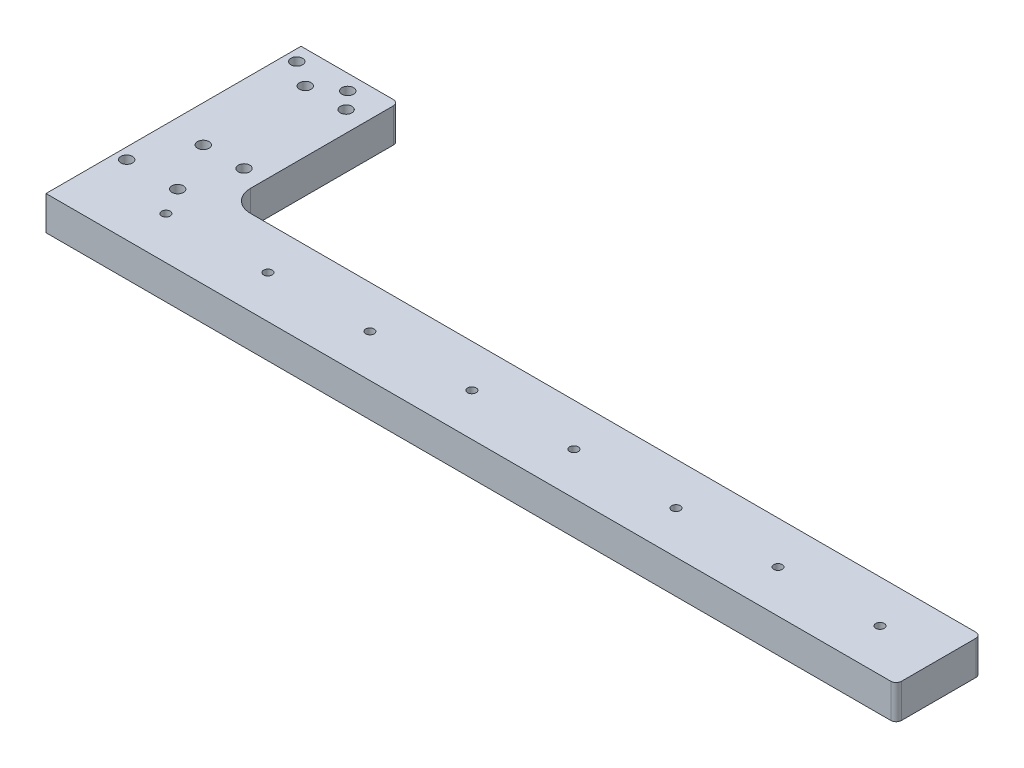
SolidWorks part; units mm, degrees
material "Low Carbon Steel"
ref_plane "Front Plane" through (0, 0, 0) normal (0, 0, 1) x (1, 0, 0)
ref_plane "Top Plane" through (0, 0, 0) normal (0, 1, 0) x (1, 0, 0)
ref_plane "Right Plane" through (0, 0, 0) normal (1, 0, 0) x (0, 0, -1)
sketch "Sketch1" plane through (0, 0, 0) normal (0, 1, 0) x (1, 0, 0)
  line L1 (0, 0) -> (496.825, 0)
  line L2 (0, 0) -> (0, 150)
  line L3 (0, 150) -> (54.325, 150)
  line L4 (500, 3.175) -> (500, 46.825)
  line L7 (496.825, 50) -> (70.2, 50)
  line L8 (57.5, 146.825) -> (57.5, 62.7)
  arc A0 (70.2, 50) -> (57.5, 62.7) centre (70.2, 62.7) cw
  arc A1 (496.825, 0) -> (500, 3.175) centre (496.825, 3.175) ccw
  arc A2 (500, 46.825) -> (496.825, 50) centre (496.825, 46.825) ccw
  arc A3 (57.5, 146.825) -> (54.325, 150) centre (54.325, 146.825) ccw
  point P12 (500, 0)
  dimension "D5" = 12.7
  dimension "D6" = 3.175
  dimension "D1" = 500
  dimension "D2" = 150
  dimension "D3" = 50
  dimension "D4" = 57.5
extrude "Boss-Extrude1" add sketch "Sketch1" along normal mid plane 20
hole_wizard "M6 Tapped Hole2" positions "Sketch2" profile "Sketch3" tap size "M6" standard "Peddi DIN"
sketch "Sketch2" plane through (0, 10, 0) normal (0, 1, 0) x (1, 0, 0)
  line L0 (0, 150) -> (0, 0) construction
  line L1 (0, 0) -> (496.825, 0) construction
  point P0 (45.5, 25)
  dimension "D1" = 45.5
  dimension "D2" = 25
cosmetic thread "Hole Thread1" parameters "D2"=6
sketch "Sketch3" plane through (45.5, 10, -25) normal (1, 0, 0) x (0, 0, 1)
  line L0 (0, 0) -> (0, 29.493)
  line L1 (0, 29.493) -> (2.5, 27.9908)
  line L2 (2.5, 27.9908) -> (2.5, 0)
  line L5 (2.5, 0) -> (0, 0)
  line L10 (0, 29.493) -> (-2.5, 27.9908) construction
  line L11 (0, -6.35) -> (0, 107.95) construction
  dimension "Tap Drill Dia." = 5
  dimension "Tap Drill Depth" = 27.9908
  dimension "Drill Angle" = 118
pattern_linear "LPattern2" count 8 spacing 60 along (1, 0, 0) of "M6 Tapped Hole2"
cosmetic thread "Hole Thread2" parameters "D2"=6
cosmetic thread "Hole Thread3" parameters "D2"=6
cosmetic thread "Hole Thread4" parameters "D2"=6
cosmetic thread "Hole Thread5" parameters "D2"=6
cosmetic thread "Hole Thread6" parameters "D2"=6
cosmetic thread "Hole Thread7" parameters "D2"=6
cosmetic thread "Hole Thread8" parameters "D2"=6
hole_wizard "M8 Tapped Hole2" positions "Sketch4" profile "Sketch5" tap size "M8" standard "Peddi DIN" end condition through all
sketch "Sketch4" plane through (0, 10, 0) normal (0, 1, 0) x (1, 0, 0)
  line L0 (45.5, 71) -> (45.5, 25) construction
  circle A0 centre (45.5, 25) radius 2.5 construction
  point P0 (45.5, 131)
  point P2 (21.5, 131)
  point P4 (45.5, 71)
  point P6 (21.5, 71)
  dimension "D3" = 46
  dimension "D1" = 24
  dimension "D2" = 60
cosmetic thread "Hole Thread9" parameters "D2"=8
cosmetic thread "Hole Thread10" parameters "D2"=8
cosmetic thread "Hole Thread11" parameters "D2"=8
cosmetic thread "Hole Thread12" parameters "D2"=8
sketch "Sketch5" plane through (45.5, 10, -131) normal (1, 0, 0) x (0, 0, 1)
  line L0 (0, 0) -> (0, 20)
  line L1 (0, 20) -> (3.4, 20)
  line L2 (3.4, 20) -> (3.4, 0)
  line L5 (3.4, 0) -> (0, 0)
  line L11 (0, -6.35) -> (0, 107.95) construction
  dimension "Thru Tap Drill Dia." = 6.8
  dimension "Thru Tap Drill Depth" = 20
hole_wizard "Ø6.8 (6.8) Diameter Hole1" positions "Sketch6" profile "Sketch7" hole size "Ø6.8" standard "Peddi DIN"
sketch "Sketch6" plane through (0, 10, 0) normal (0, 1, 0) x (1, 0, 0)
  circle A0 centre (45.5, 25) radius 2.5 construction
  point P0 (36.5, 140.95)
  point P2 (6.5, 140.95)
  point P4 (6.5, 40.95)
  point P6 (36.5, 40.95)
  dimension "D1" = 9
  dimension "D2" = 30
  dimension "D3" = 100
  dimension "D4" = 15.95
sketch "Sketch7" plane through (36.5, 10, -140.95) normal (1, 0, 0) x (0, 0, 1)
  line L0 (0, 0) -> (0, 10.0429)
  line L1 (0, 10.0429) -> (3.4, 8)
  line L2 (3.4, 8) -> (3.4, 0)
  line L5 (3.4, 0) -> (0, 0)
  line L10 (0, 10.0429) -> (-3.4, 8) construction
  line L11 (0, -6.35) -> (0, 107.95) construction
  dimension "Hole Dia." = 6.8
  dimension "Hole Depth" = 8
  dimension "Drill Angle" = 118
hole_wizard "M6 Tapped Hole1" positions "Sketch8" profile "Sketch9" tap size "M6" standard "Peddi DIN" end condition through all
sketch "Sketch8" plane through (0, 10, 0) normal (0, 1, 0) x (1, 0, 0)
  point P0 (6.5, 140.95)
  point P3 (36.5, 140.95)
  point P6 (36.5, 40.95)
  point P9 (6.5, 40.95)
sketch "Sketch9" plane through (6.5, 10, -140.95) normal (1, 0, 0) x (0, 0, 1)
  line L0 (0, 0) -> (0, 20)
  line L1 (0, 20) -> (2.5, 20)
  line L2 (2.5, 20) -> (2.5, 0)
  line L5 (2.5, 0) -> (0, 0)
  line L11 (0, -6.35) -> (0, 107.95) construction
  dimension "Thru Tap Drill Dia." = 5
  dimension "Thru Tap Drill Depth" = 20
cosmetic thread "Hole Thread13" parameters "D2"=6
cosmetic thread "Hole Thread14" parameters "D2"=6
cosmetic thread "Hole Thread15" parameters "D2"=6
cosmetic thread "Hole Thread16" parameters "D2"=6
sketch "RAIL ZONE" plane through (0, 10, 0) normal (0, 1, 0) x (1, 0, 0)
  line L0 (500, 3.175) -> (500, 46.825) construction
  line L1 (500, 40.875) -> (13.75, 40.875)
  line L2 (500, 40.875) -> (500, 9.125)
  line L3 (500, 9.125) -> (13.75, 9.125)
  line L4 (13.75, 40.875) -> (13.75, 9.125)
  line L5 (45.5, 25) -> (13.75, 25) construction
  dimension "D1" = 31.75
  dimension "D2" = 31.75
sketch "MTG BAR ZONE" plane through (0, -10, 0) normal (0, -1, 0) x (1, 0, 0)
  line L0 (0, -150) -> (0, 0) construction
  line L1 (0, -31.9) -> (57.5, -31.9)
  line L2 (0, -31.9) -> (0, -50)
  line L3 (0, -50) -> (57.5, -50)
  line L4 (57.5, -31.9) -> (57.5, -50)
  line L5 (54.325, -150) -> (0, -150) construction
  line L6 (0, -131.9) -> (57.5, -131.9)
  line L7 (0, -131.9) -> (0, -150)
  line L8 (0, -150) -> (57.5, -150)
  line L9 (57.5, -131.9) -> (57.5, -150)
  line L10 (57.5, -62.7) -> (57.5, -146.825) construction
  line L11 (6.5, -40.95) -> (0, -40.95) construction
  line L12 (6.5, -140.95) -> (0, -140.95) construction
other "Freeze***"
